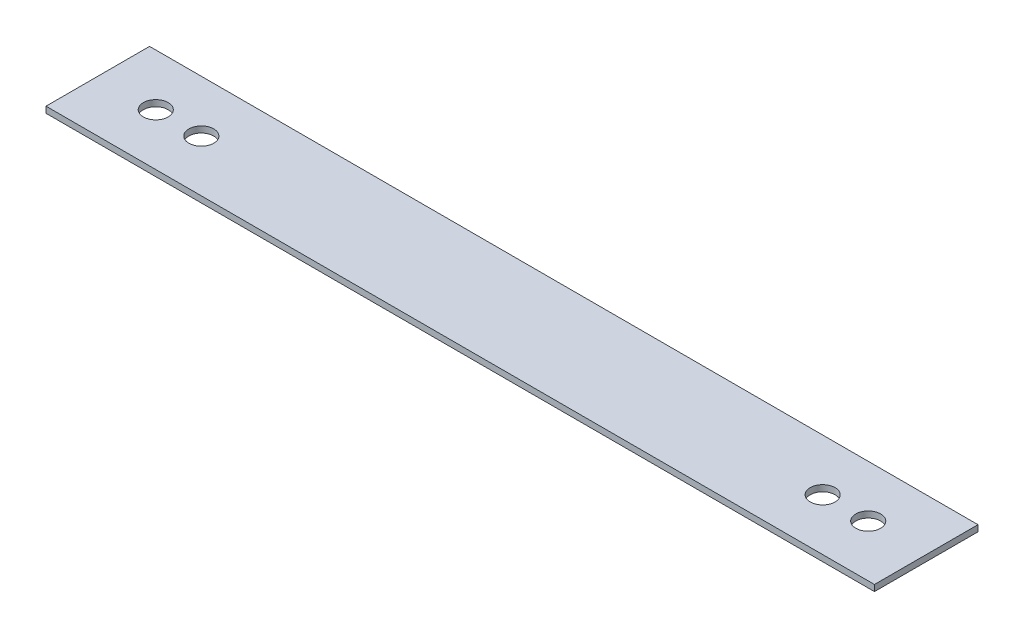
SolidWorks part; units mm, degrees
material "A-玻璃纤维"
ref_plane "前视基准面" through (0, 0, 0) normal (0, 0, 1) x (1, 0, 0)
ref_plane "上视基准面" through (0, 0, 0) normal (0, 1, 0) x (1, 0, 0)
ref_plane "右视基准面" through (0, 0, 0) normal (1, 0, 0) x (0, 0, -1)
sketch "草图1" plane through (0, 0, 0) normal (0, 1, 0) x (1, 0, 0)
  line L1 (200, 25) -> (-200, 25)
  line L2 (200, 25) -> (200, -25)
  line L3 (200, -25) -> (-200, -25)
  line L4 (-200, 25) -> (-200, -25)
  line L5 (200, 25) -> (-200, -25) construction
  line L6 (200, -25) -> (-200, 25) construction
  point P0 (0, 0)
  dimension "D1" = 400
  dimension "D2" = 50
extrude "凸台-拉伸1" add sketch "草图1" along normal blind 3
sketch "草图2" plane through (0, 3, 0) normal (0, 1, 0) x (1, 0, 0)
  line L0 (-227.7022, 0) -> (221.71, 0) construction
  circle A0 centre (-172, 0) radius 6
  circle A1 centre (-150, 0) radius 6
  circle A2 centre (150, 0) radius 6
  circle A3 centre (172, 0) radius 6
  point P13 (-299.6081, 157.7223)
  dimension "D1" = 12
  dimension "D2" = 12
  dimension "D3" = 12
  dimension "D4" = 12
  dimension "D5" = 22
  dimension "D6" = 22
  dimension "D7" = 150
  dimension "D8" = 150
extrude "切除-拉伸1" cut sketch "草图2" against normal blind 8
